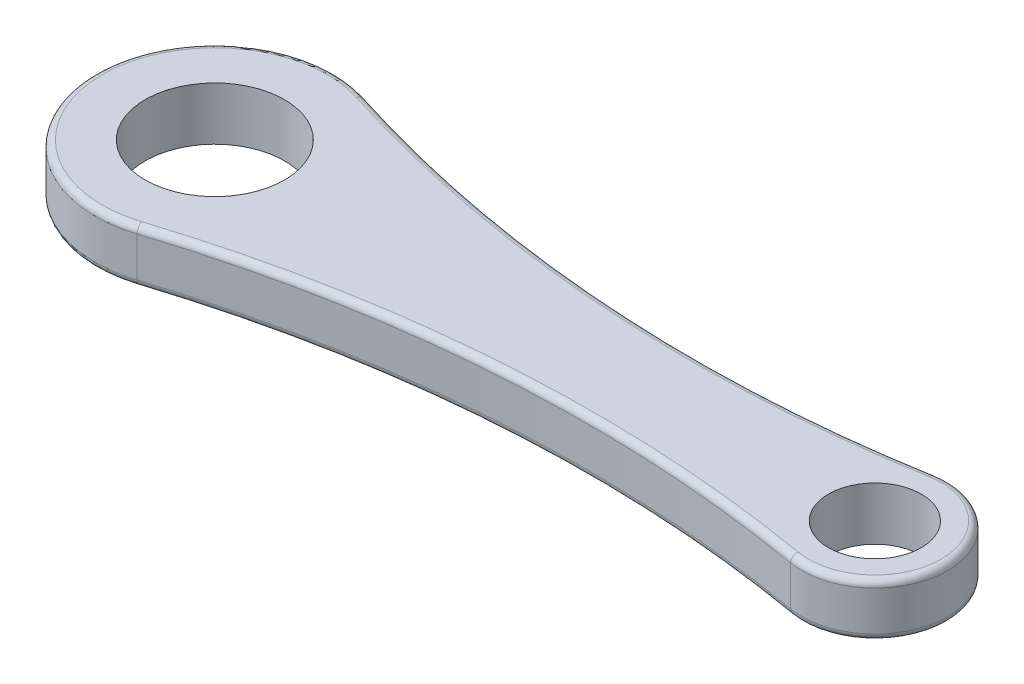
SolidWorks part; units mm, degrees
ref_plane "前视基准面" through (0, 0, 0) normal (0, 0, 1) x (1, 0, 0)
ref_plane "上视基准面" through (0, 0, 0) normal (0, 1, 0) x (1, 0, 0)
ref_plane "右视基准面" through (0, 0, 0) normal (1, 0, 0) x (0, 0, -1)
sketch "草图1" plane through (0, 0, 0) normal (0, 1, 0) x (1, 0, 0)
  line L0 (0, 0) -> (49.75, 0) construction
  circle A0 centre (0, 0) radius 5.25
  circle A1 centre (49.75, 0) radius 3.5
  arc A2 (2.726, 8.5772) -> (2.726, -8.5772) centre (0, 0) ccw
  arc A3 (48.8145, -5.4199) -> (48.8145, 5.4199) centre (49.75, 0) ccw
  arc A4 (2.726, 8.5772) -> (48.8145, 5.4199) centre (32.2405, 101.4447) ccw
  arc A5 (2.726, -8.5772) -> (48.8145, -5.4199) centre (32.2405, -101.4447) cw
  dimension "D1" = 18
  dimension "D2" = 11
  dimension "D3" = 7
  dimension "D4" = 10.5
  dimension "D5" = 41
  dimension "D6" = 8
extrude "凸台-拉伸1" add sketch "草图1" along normal blind 4
fillet "圆角1" radius 0.5 8 edges at (-9, 0, 0) (25.5804, 0, -4.2279) (55.25, 0, 0) (-9, 4, 0) (25.5804, 4, -4.2279) (55.25, 4, 0) (25.5804, 0, 4.2279) (25.5804, 4, 4.2279)
